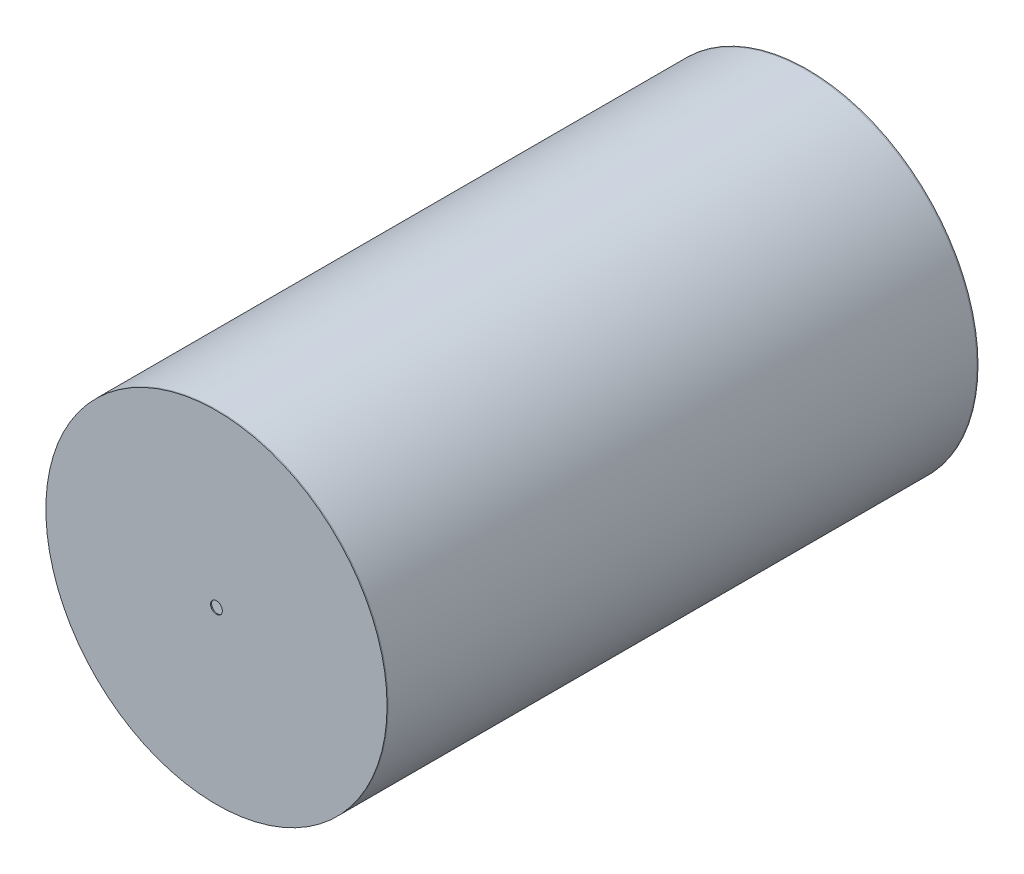
SolidWorks part; units mm, degrees
ref_plane "Front Plane" through (0, 0, 0) normal (0, 0, 1) x (1, 0, 0)
ref_plane "Top Plane" through (0, 0, 0) normal (0, 1, 0) x (1, 0, 0)
ref_plane "Right Plane" through (0, 0, 0) normal (1, 0, 0) x (0, 0, -1)
sketch "Sketch1" plane through (0, 0, 0) normal (0, 0, 1) x (1, 0, 0)
  circle A0 centre (0, 0) radius 332
  dimension "D1" = 664
extrude "Boss-Extrude1" add sketch "Sketch1" along normal blind 2
sketch "Sketch2" plane through (0, 0, 2) normal (0, 0, 1) x (1, 0, 0)
  circle A0 centre (0, 0) radius 330
  circle A1 centre (0, 0) radius 332
  dimension "D1" = 664
  dimension "D2" = 660
extrude "Boss-Extrude2" add sketch "Sketch2" along normal blind 1145.92 separate body
sketch "Sketch4" plane through (0, 0, 1147.92) normal (0, 0, 1) x (1, 0, 0)
  circle A0 centre (0, 0) radius 332
  dimension "D1" = 664
extrude "Boss-Extrude4" add sketch "Sketch4" along normal blind 2 separate body
sketch "Sketch5" plane through (0, 0, 1149.92) normal (0, 0, 1) x (1, 0, 0)
  circle A0 centre (0, 0) radius 11.45
  dimension "D1" = 22.9
extrude "Cut-Extrude1" cut sketch "Sketch5" against normal up to next (2 mm away)
